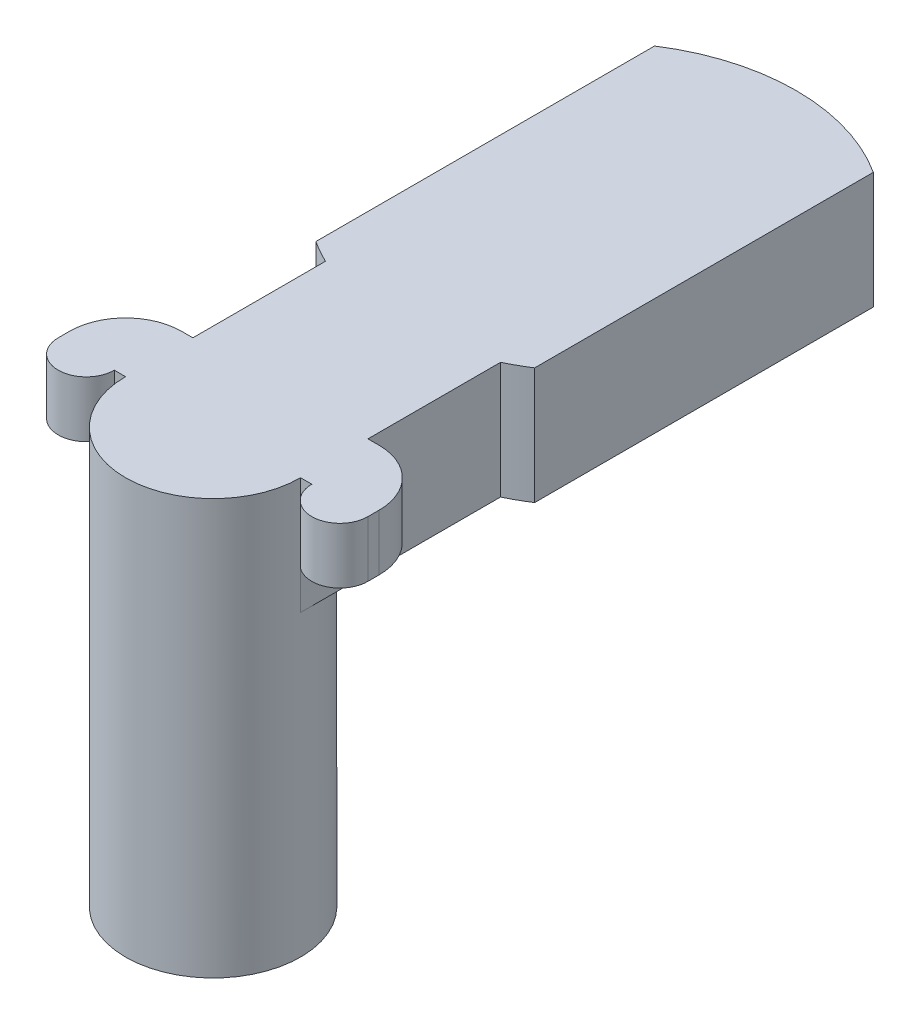
SolidWorks part; units mm, degrees
ref_plane "Front Plane" through (0, 0, 0) normal (0, 0, 1) x (1, 0, 0)
ref_plane "Top Plane" through (0, 0, 0) normal (0, 1, 0) x (1, 0, 0)
ref_plane "Right Plane" through (0, 0, 0) normal (1, 0, 0) x (0, 0, -1)
sketch "Sketch3" plane through (0, 0, 0) normal (0, 1, 0) x (1, 0, 0)
  line L0 (-4.875, 7.5453) -> (-4.875, -7.5453)
  line L1 (4.875, 7.5453) -> (4.875, -7.5453)
  arc A0 (-4.875, -7.5453) -> (4.875, -7.5453) centre (0, 0) ccw
  arc A1 (4.875, 7.5453) -> (-4.875, 7.5453) centre (0, 0) ccw
  dimension "D1" = 9.75
extrude "Boss-Extrude1" add sketch "Sketch3" along normal blind 5.2
sketch "Sketch5" plane through (0, 0, 0) normal (0, 0, 1) x (1, 0, 0)
  line L0 (0, 5.2) -> (0, 0) construction
  line L1 (4.875, 5.2) -> (-4.875, 5.2) construction
  line L3 (-3.9, 0) -> (3.9, 0)
  line L4 (-3.9, 0) -> (-3.9, 5.2)
  line L5 (-3.9, 5.2) -> (3.9, 5.2)
  line L6 (3.9, 0) -> (3.9, 5.2)
  line L7 (-3.9, 0) -> (3.9, 5.2) construction
  line L8 (-3.9, 5.2) -> (3.9, 0) construction
  point P5 (0, 2.6)
  dimension "D1" = 7.8
extrude "Boss-Extrude2" add sketch "Sketch5" along normal blind 17
sketch "Sketch6" plane through (0, 5.2, 0) normal (0, 1, 0) x (1, 0, 0)
  line L0 (3.9, -17) -> (-3.9, -17) construction
  circle A0 centre (0, -17) radius 3.9
extrude "Boss-Extrude3" add sketch "Sketch6" against normal blind 18.5
sketch "Sketch7" plane through (0, 5.2, 0) normal (0, 1, 0) x (1, 0, 0)
  line L1 (3.9, -17) -> (3.9, -8.0924) construction
  line L6 (-4.4, -14) -> (4.4, -14)
  line L19 (0, -17) -> (0, 49983) construction
  line L28 (0, -14) -> (0, -17)
  line L29 (0, -14) -> (0, -17)
  line L30 (-4.4, -17) -> (4.4, -17)
  line L31 (6.9, -16.5) -> (6.9, -17)
  line L32 (-6.9, -16.5) -> (-6.9, -17)
  arc A0 (4.4, -17) -> (6.9, -17) centre (5.65, -17) ccw
  arc A1 (-4.4, -17) -> (-6.9, -17) centre (-5.65, -17) cw
  arc A2 (-6.9, -16.5) -> (-4.4, -14) centre (-4.4, -16.5) cw
  arc A3 (4.4, -14) -> (6.9, -16.5) centre (4.4, -16.5) cw
  point P3 (0, -17)
  point P14 (-6.9, -14)
  point P21 (6.9, -14)
  dimension "D1" = 3
  dimension "D2" = 2.5
  dimension "D3" = 2.5
extrude "Boss-Extrude4" add sketch "Sketch7" against normal blind 2.5
sketch "Sketch8" plane through (0, -13.3, 0) normal (0, -1, 0) x (1, 0, 0)
  circle A0 centre (0, 17) radius 1.6
  dimension "D1" = 3.2
extrude "Cut-Extrude1" cut sketch "Sketch8" against normal blind 5
